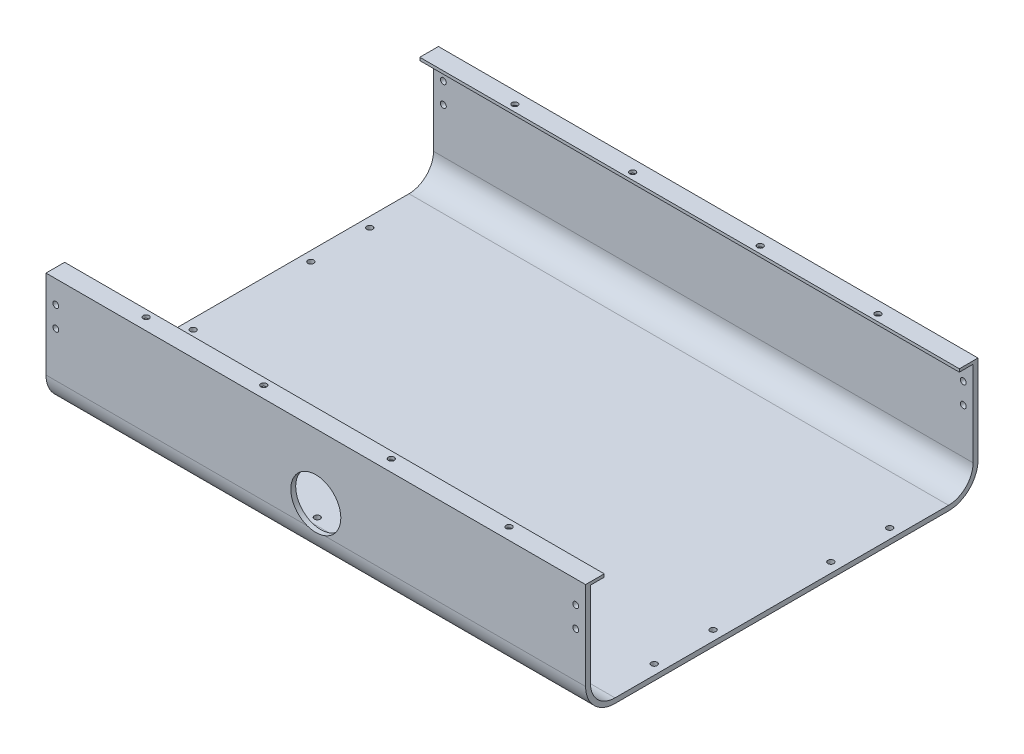
SolidWorks part; units mm, degrees
ref_plane "前视基准面" through (0, 0, 0) normal (0, 0, 1) x (1, 0, 0)
ref_plane "上视基准面" through (0, 0, 0) normal (0, 1, 0) x (1, 0, 0)
ref_plane "右视基准面" through (0, 0, 0) normal (1, 0, 0) x (0, 0, -1)
sketch "草图1" plane through (0, 0, 0) normal (1, 0, 0) x (0, 0, -1)
  line L0 (0, 0) -> (-170, 0)
  line L1 (-200, 30) -> (-200, 120)
  line L2 (-200, 120) -> (-181, 120)
  line L3 (-181, 120) -> (-181, 117)
  line L4 (195, 30) -> (195, 115)
  line L5 (0, 5) -> (170, 5)
  line L6 (0, 5) -> (-170, 5)
  line L7 (0, 29.4391) -> (0, -23.1414) construction
  line L8 (-195, 30) -> (-195, 115)
  line L9 (-181, 117) -> (-195, 117)
  line L10 (-195, 117) -> (-195, 115)
  line L11 (195, 117) -> (195, 115)
  line L12 (200, 120) -> (181, 120)
  line L13 (200, 30) -> (200, 120)
  line L14 (0, 0) -> (170, 0)
  line L15 (181, 117) -> (195, 117)
  line L16 (181, 120) -> (181, 117)
  line L18 (-195, 115) -> (-181, 115) construction
  line L19 (195, 115) -> (181, 115) construction
  arc A0 (-170, 0) -> (-200, 30) centre (-170, 30) cw
  arc A1 (170, 5) -> (195, 30) centre (170, 30) ccw
  arc A2 (-170, 5) -> (-195, 30) centre (-170, 30) cw
  arc A3 (170, 0) -> (200, 30) centre (170, 30) ccw
  point P0 (200, 0)
  point P8 (-200, 0)
  dimension "D2" = 30
  dimension "D1" = 200
  dimension "D3" = 90
  dimension "D4" = 19
  dimension "D6" = 3
  dimension "D5" = 5
extrude "凸台-拉伸1" add sketch "草图1" along normal mid plane 550 contours L2 L3 L9 L10 L8 A2 L6 L5 A1 L4 L11 L15 L16 L12 L13 A3 L14 L0 A0 L1
sketch "草图6" plane through (0, 0, 200) normal (0, 0, 1) x (1, 0, 0)
  line L0 (275, 0) -> (-275, 0) construction
  circle A0 centre (0, 54) radius 25.5
  dimension "D1" = 51
  dimension "D2" = 54
extrude "切除-拉伸3" cut sketch "草图6" against normal blind 50
sketch "草图11" plane through (0, 0, 0) normal (0, -1, 0) x (1, 0, 0)
  line L0 (275, 170) -> (-275, 170) construction
  line L1 (0, 0) -> (0, 220.2263) construction
  circle A0 centre (-23, 125) radius 2
  circle A1 centre (-36, 162.5) radius 3
  circle A2 centre (-36, 87.5) radius 3
  circle A3 centre (36, 87.5) radius 3
  circle A4 centre (36, 162.5) radius 3
  circle A5 centre (23, 125) radius 2
  dimension "D1" = 6
  dimension "D3" = 6
  dimension "D4" = 4
  dimension "D2" = 7.5
  dimension "D5" = 23
  dimension "D6" = 36
  dimension "D7" = 37.5
  dimension "D8" = 75
extrude "切除-拉伸4" cut sketch "草图11" against normal blind 10
sketch "草图12" plane through (0, 0, -200) normal (0, 0, -1) x (-1, 0, 0)
  line L0 (-275, 30) -> (-275, 120) construction
  line L1 (-275, 30) -> (275, 30) construction
  line L2 (-275, 120) -> (275, 120) construction
  circle A0 centre (-265, 97) radius 3
  circle A1 centre (-265, 76) radius 3
  dimension "D1" = 6
  dimension "D2" = 6
  dimension "D3" = 10
  dimension "D4" = 46
  dimension "D5" = 23
extrude "切除-拉伸5" cut sketch "草图12" against normal through all
mirror "镜向1" about plane through (0, 0, 0) normal (1, 0, 0) of "切除-拉伸5"
sketch "草图13" plane through (0, 0, 0) normal (0, -1, 0) x (1, 0, 0)
  line L0 (-275, -170) -> (-275, 170) construction
  line L1 (0, 0) -> (-534.5918, 0) construction
  circle A0 centre (-265, 120) radius 3
  circle A1 centre (-265, 60) radius 3
  circle A2 centre (-265, -120) radius 3
  circle A3 centre (-265, -60) radius 3
  point P13 (0, 0)
  dimension "D1" = 6
  dimension "D2" = 120
  dimension "D3" = 6
  dimension "D6" = 6
  dimension "D7" = 6
  dimension "D4" = 10
  dimension "D5" = 120
  dimension "D8" = 60
  dimension "D9" = 60
extrude "切除-拉伸6" cut sketch "草图13" against normal blind 13
mirror "镜向2" about plane through (0, 0, 0) normal (1, 0, 0) of "切除-拉伸6"
sketch "草图14" plane through (0, 120, 0) normal (0, 1, 0) x (1, 0, 0)
  line L0 (275, -200) -> (-275, -200) construction
  line L1 (0, 0) -> (0, -9.0609) construction
  line L2 (-297.0034, 0) -> (0, 0) construction
  line L3 (-275, -200) -> (-275, -181) construction
  line L4 (0, 0) -> (0, -237.8431) construction
  circle A0 centre (-185, -188) radius 3
  circle A1 centre (-65, -188) radius 3
  circle A2 centre (65, -188) radius 3
  circle A3 centre (185, -188) radius 3
  circle A4 centre (-185, -188) radius 3
  circle A5 centre (-65, -188) radius 3
  circle A6 centre (65, -188) radius 3
  circle A7 centre (185, -188) radius 3
  circle A8 centre (185, 188) radius 3
  circle A9 centre (65, 188) radius 3
  circle A10 centre (185, 188) radius 3
  circle A11 centre (65, 188) radius 3
  circle A12 centre (-65, 188) radius 3
  circle A13 centre (-185, 188) radius 3
  circle A14 centre (-65, 188) radius 3
  circle A15 centre (-185, 188) radius 3
  dimension "D1" = 6
  dimension "D2" = 6
  dimension "D3" = 12
  dimension "D4" = 90
  dimension "D5" = 120
extrude "切除-拉伸7" cut sketch "草图14" against normal blind 13 contours A0 | A1 | A2 | A3 | A8 | A9 | A12 | A13
